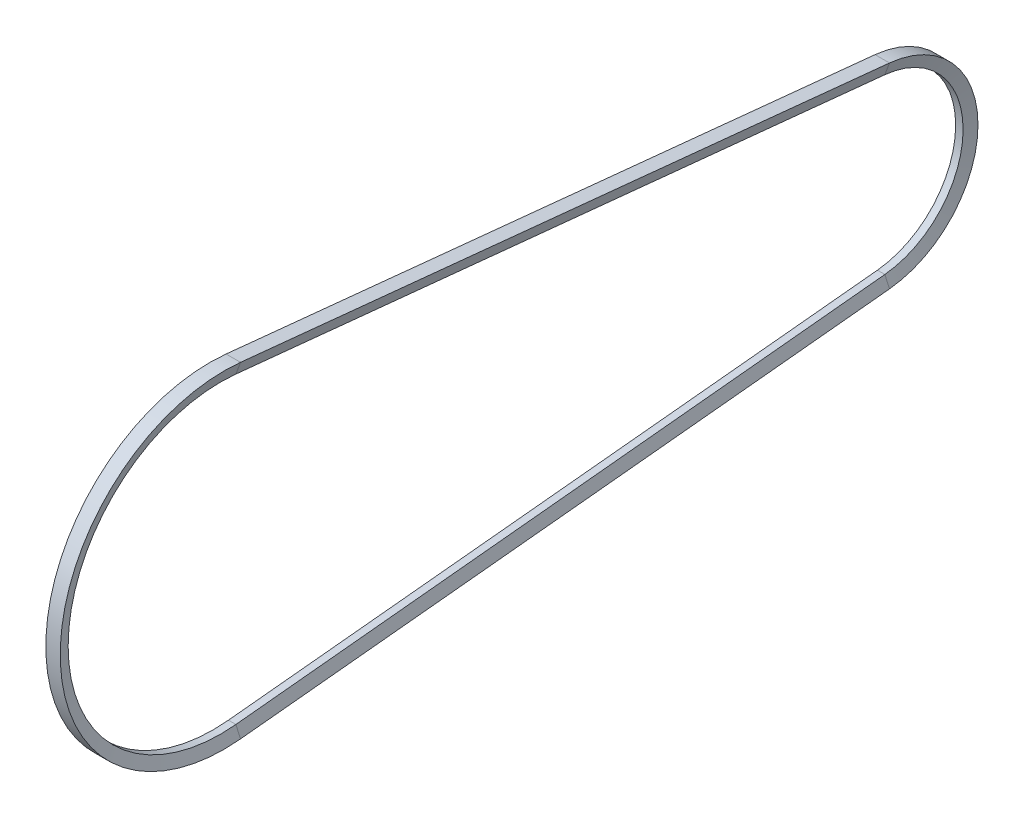
SolidWorks part; units mm, degrees
ref_plane "前视基准面" through (0, 0, 0) normal (0, 0, 1) x (1, 0, 0)
ref_plane "上视基准面" through (0, 0, 0) normal (0, 1, 0) x (1, 0, 0)
ref_plane "右视基准面" through (0, 0, 0) normal (1, 0, 0) x (0, 0, -1)
sketch "草图1" plane through (0, 0, 0) normal (1, 0, 0) x (0, 0, -1)
  line L0 (12.5, 124.3734) -> (507.5, 74.6241)
  line L1 (12.5, -124.3734) -> (507.5, -74.6241)
  line L2 (0, 0) -> (500, 0) construction
  arc A0 (12.5, 124.3734) -> (12.5, -124.3734) centre (0, 0) ccw
  arc A1 (507.5, -74.6241) -> (507.5, 74.6241) centre (500, 0) ccw
  dimension "D1" = 125
  dimension "D2" = 75
  dimension "D3" = 500
sketch "草图2" plane through (0, 0, 0) normal (0, 0, 1) x (1, 0, 0)
  line L0 (-5.5, 125) -> (5.5, 125)
  line L1 (5.5, 125) -> (2.8401, 116.3)
  line L2 (2.8401, 116.3) -> (-2.8401, 116.3)
  line L3 (-2.8401, 116.3) -> (-5.5, 125)
  line L4 (0, 116.3) -> (0, 125) construction
  line L5 (0, -125) -> (0, 125) construction
  dimension "D1" = 11
  dimension "D2" = 8.7
  dimension "D3" = 34
sweep "扫描1" add profiles "草图2" path "草图1"
equation "\"D3@草图1\" = \"D1@距离1@孔板轮_孔板轮.Assembly\""
equation "\"D1@草图2\" = \"bd@草图1@大带轮_孔板轮.Part\" "
equation "\"D2@草图2\" = \"hf@草图1@大带轮_孔板轮.Part\" "
equation "\"D3@草图2\" = \"槽轮角@草图1@大带轮_孔板轮.Part\" "
equation " \"D2@草图1\" = \"dd@草图1@小带轮_孔板轮.Part\"/2"
equation "\"D1@草图1\" = \"dd@草图1@大带轮_孔板轮.Part\" /2"
